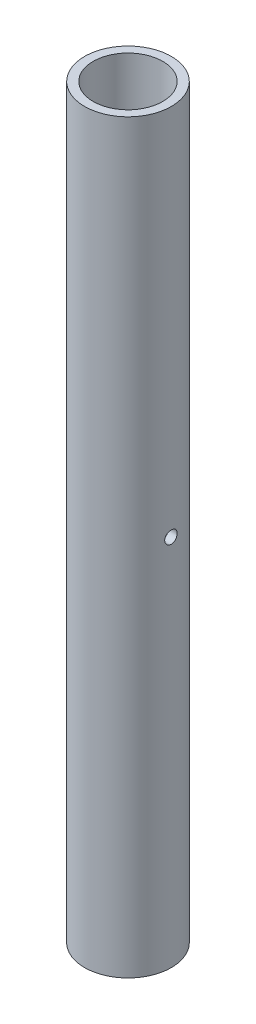
SolidWorks part; units mm, degrees
material "PVC Rigid"
ref_plane "Front Plane" through (0, 0, 0) normal (0, 0, 1) x (1, 0, 0)
ref_plane "Top Plane" through (0, 0, 0) normal (0, 1, 0) x (1, 0, 0)
ref_plane "Right Plane" through (0, 0, 0) normal (1, 0, 0) x (0, 0, -1)
sketch "Sketch2" plane through (0, 0, 0) normal (0, 1, 0) x (1, 0, 0)
  circle A0 centre (0, 0) radius 17.45
  circle A1 centre (0, 0) radius 14
  dimension "D1" = 28
  dimension "D2" = 34.9
extrude "Boss-Extrude1" add sketch "Sketch2" against normal blind 300
ref_plane "Plane1" through (17.45, 0, 0) normal (1, 0, 0) x (0, 0, -1)
hole_wizard "Tap Drill for M6x1.0 Tap2" positions "Sketch5" profile "Sketch6" hole size "M6x1.0" standard "ANSI Metric" end condition through all
sketch "Sketch5" plane through (17.45, 0, 0) normal (1, 0, 0) x (0, 0, -1)
  line L0 (-17.45, 0) -> (-17.45, -300) construction
  point P0 (0, -150)
  dimension "D1" = 150
  dimension "D2" = 17.45
sketch "Sketch6" plane through (17.45, -150, 0) normal (0, 1, 0) x (0, 0, -1)
  line L0 (0, 0) -> (0, 34.9)
  line L1 (0, 34.9) -> (2.5, 34.9)
  line L2 (2.5, 34.9) -> (2.5, 0)
  line L5 (2.5, 0) -> (0, 0)
  line L11 (0, -6.35) -> (0, 107.95) construction
  dimension "Thru Hole Dia." = 5
  dimension "Thru Hole Depth" = 34.9
